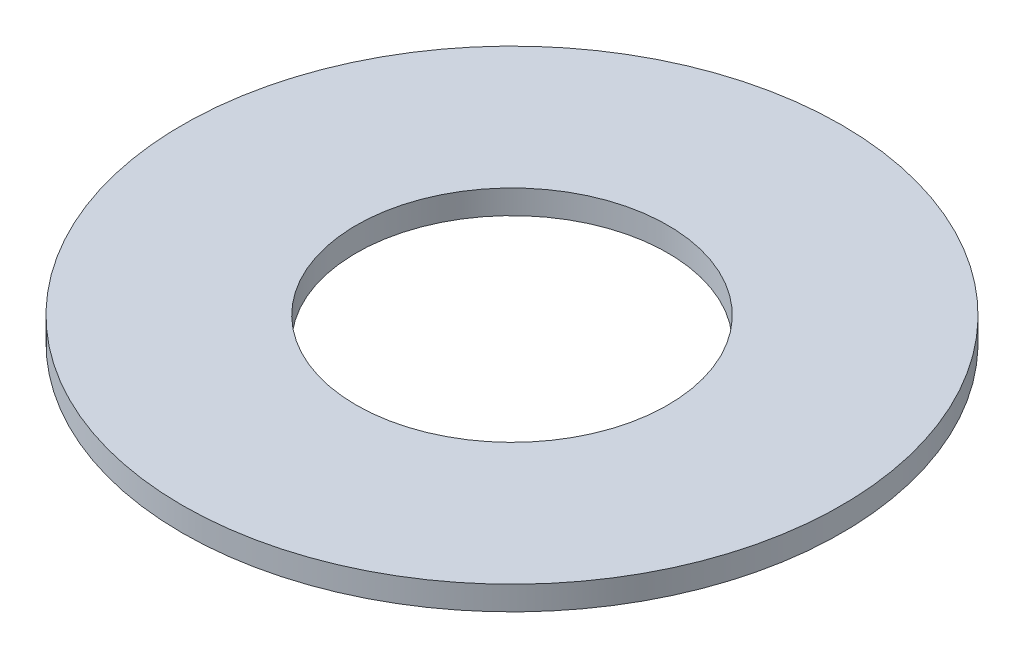
SolidWorks part; units mm, degrees
ref_plane "前视基准面" through (0, 0, 0) normal (0, 0, 1) x (1, 0, 0)
ref_plane "上视基准面" through (0, 0, 0) normal (0, 1, 0) x (1, 0, 0)
ref_plane "右视基准面" through (0, 0, 0) normal (1, 0, 0) x (0, 0, -1)
other "Configuration Table"
sketch "草图1" plane through (0, 0, 0) normal (0, 1, 0) x (1, 0, 0)
  circle A0 centre (0, 0) radius 5.5
  circle A1 centre (0, 0) radius 2.6
  dimension "D1" = 11
  dimension "D2" = 5.2
extrude "凸台-拉伸1" add sketch "草图1" along normal blind 0.4
